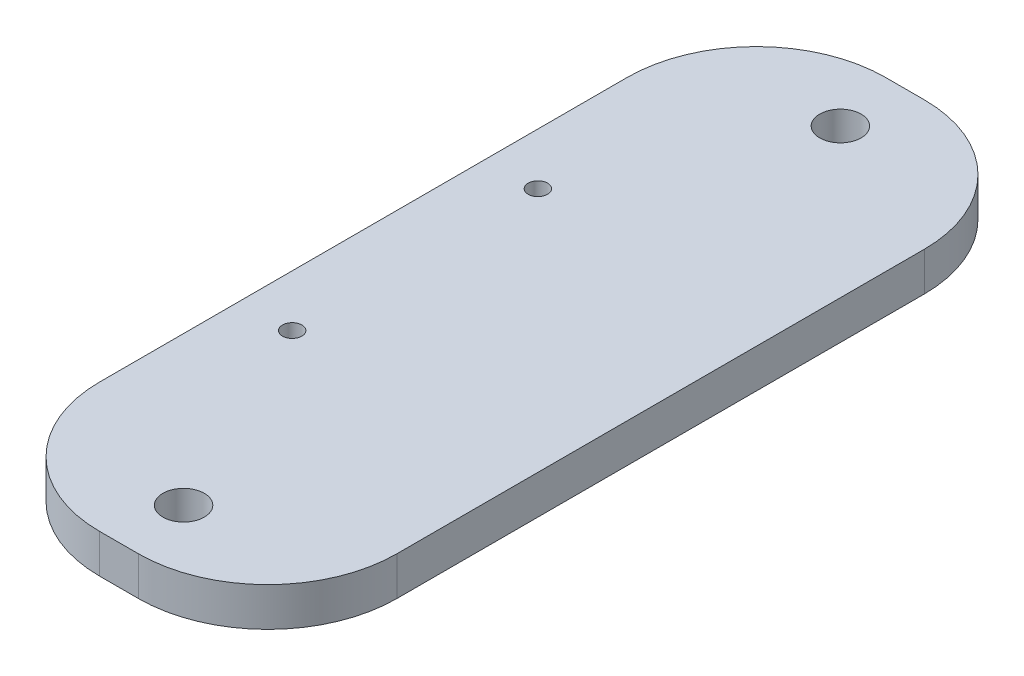
SolidWorks part; units mm, degrees
ref_plane "Front Plane" through (0, 0, 0) normal (0, 0, 1) x (1, 0, 0)
ref_plane "Top Plane" through (0, 0, 0) normal (0, 1, 0) x (1, 0, 0)
ref_plane "Right Plane" through (0, 0, 0) normal (1, 0, 0) x (0, 0, -1)
other "Configuration Table"
sketch "Sketch1" plane through (0, 0, 0) normal (0, 1, 0) x (1, 0, 0)
  line L0 (0, 0) -> (-7.5, 0) construction
  line L1 (-11.5, 30.4) -> (11.5, 30.4)
  line L2 (-11.5, 30.4) -> (-11.5, -30.4)
  line L3 (-11.5, -30.4) -> (11.5, -30.4)
  line L4 (11.5, 30.4) -> (11.5, -30.4)
  line L5 (-11.5, 30.4) -> (11.5, -30.4) construction
  line L6 (-11.5, -30.4) -> (11.5, 30.4) construction
  line L7 (-7.5, 9.5) -> (-7.5, -9.5) construction
  line L8 (0, 0) -> (0, 12.7) construction
  line L9 (0, 12.7) -> (0, 25.4) construction
  line L10 (0, 0) -> (0, -12.7) construction
  line L11 (0, -12.7) -> (0, -25.4) construction
  line L12 (0, 25.4) -> (0, 30.4) construction
  line L13 (-7.5, 0) -> (-11.5, 0) construction
  line L14 (-7.5, 10.5) -> (-7.5, -10.5) construction
  line L15 (-7.5, 0) -> (11.5, 0) construction
  circle A0 centre (-7.5, 9.5) radius 0.75
  circle A1 centre (-7.5, -9.5) radius 0.75
  circle A2 centre (0, 25.4) radius 1.6
  circle A3 centre (0, -25.4) radius 1.6
  point P0 (0, 0)
  point P11 (-7.5, 0)
  point P22 (-7.5, 0)
  point P25 (0, 0)
  point P27 (-16.9359, 0)
  point P28 (0, 0)
  point P29 (0, 0)
  point P30 (0, 0)
  point P31 (0, 0)
  point P32 (6.2082, 0)
  point P33 (10.9607, 0)
  point P34 (0, 0)
  point P35 (2, 0)
  point P36 (0, 0)
  dimension "D2" = 1.5
  dimension "D9" = 3.2
  dimension "D1" = 19
  dimension "D3" = 12.7
  dimension "D4" = 21
  dimension "D5" = 19
  dimension "D6" = 5
  dimension "D7" = 4
  dimension "D8" = 2
extrude "Boss-Extrude1" add sketch "Sketch1" along normal blind 3
fillet "Fillet1" radius 10 4 edges at (11.5, 1.5, 30.4) (-11.5, 1.5, 30.4) (-11.5, 1.5, -30.4) (11.5, 1.5, -30.4)
